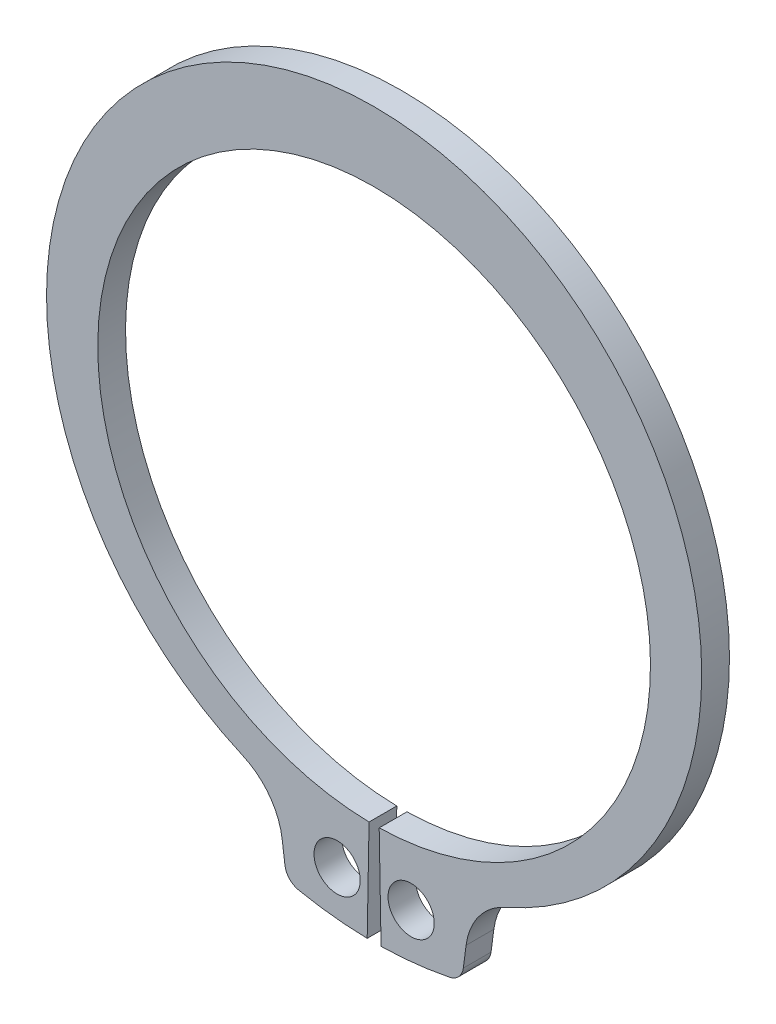
SolidWorks part; units mm, degrees
ref_plane "Plane1" through (0, 0, 0) normal (0, 0, 1) x (1, 0, 0)
ref_plane "Plane2" through (0, 0, 0) normal (0, 1, 0) x (1, 0, 0)
ref_plane "Plane3" through (0, 0, 0) normal (1, 0, 0) x (0, 0, -1)
sketch "Clipboard" plane through (0, 0, 0) normal (0, 0, 1) x (1, 0, 0)
  line L0 (0, 0) -> (3, 0)
  line L1 (0, 0) -> (0, 1.5)
  line L2 (0, 0) -> (0, -4.4)
  circle A0 centre (0, 0) radius 1
  circle A1 centre (0, 0) radius 12.5
sketch "BodySke" plane through (0, 0, 0) normal (0, 0, 1) x (1, 0, 0)
  line L0 (-1.5431, 0) -> (1.5431, 0) construction
  line L1 (0, 0) -> (0, 14.95) construction
  line L2 (0.2193, -11.948) -> (0.3, -16.3472)
  line L3 (-0.2193, -11.948) -> (-0.3, -16.3472)
  line L4 (0, 0) -> (6.8515, -14.8452) construction
  line L5 (0, 0) -> (-6.8515, -14.8452) construction
  line L7 (3.9769, -14.4667) -> (3.8561, -15.3842)
  line L8 (-3.9769, -14.4667) -> (-3.8561, -15.3842)
  circle A0 centre (0, 0) radius 11.95 construction
  arc A1 (0.2193, -11.948) -> (-0.2193, -11.948) centre (0, 0) ccw
  arc A2 (5.6362, -12.2121) -> (-5.6362, -12.2121) centre (0, 0.7842) ccw construction
  arc A3 (0.3, -16.3472) -> (3.2622, -16.0213) centre (0, 0) ccw
  arc A4 (5.6874, -12.1898) -> (3.9769, -14.4667) centre (6.8515, -14.8452) ccw
  arc A5 (-3.9769, -14.4667) -> (-5.6874, -12.1898) centre (-6.8515, -14.8452) ccw
  arc A6 (-3.2622, -16.0213) -> (-0.3, -16.3472) centre (0, 0) ccw
  arc A7 (5.6874, -12.1898) -> (-5.6874, -12.1898) centre (0, 0.7842) ccw
  arc A8 (-4.0592, -13.8421) -> (4.0592, -13.8421) centre (0, 0) ccw construction
  circle A9 centre (1.6, -14.336) radius 1
  circle A10 centre (-1.6, -14.336) radius 1
  arc A11 (3.8561, -15.3842) -> (3.2622, -16.0213) centre (3.1126, -15.2863) cw
  arc A12 (-3.8561, -15.3842) -> (-3.2622, -16.0213) centre (-3.1126, -15.2863) ccw
  point P28 (3.7876, -15.9052)
  point P31 (-3.7876, -15.9052)
  dimension "D3" = 0.75
  dimension "D2" = 15
extrude "Body" add sketch "BodySke" against normal blind 1.2
sketch "NotSke" plane through (0, 0, 0) normal (0, 0, 1) x (1, 0, 0)
  line L0 (1.6, -13.336) -> (1.6, -15.336)
  line L1 (1.6, -15.336) -> (-1.6, -15.336)
  line L2 (-1.6, -15.336) -> (-1.6, -13.336)
  line L3 (-1.6, -13.336) -> (1.6, -13.336)
  circle A0 centre (1.6, -14.336) radius 1 construction
  circle A1 centre (-1.6, -14.336) radius 1 construction
extrude "Notch" [suppressed] cut sketch "NotSke" against normal through all
sketch "UnlSke" plane through (0, 0, 0) normal (0, 0, 1) x (1, 0, 0)
  line L0 (-2.9356, -16.0843) -> (-2.1456, -11.7558)
  line L1 (2.9356, -16.0843) -> (2.1456, -11.7558)
  arc A0 (2.1456, -11.7558) -> (-2.1456, -11.7558) centre (0, 0) ccw
  arc A1 (2.9356, -16.0843) -> (-2.9356, -16.0843) centre (0, 0) ccw
  arc A2 (0.3, -16.3472) -> (3.2622, -16.0213) centre (0, 0) ccw construction
  arc A3 (0.2193, -11.948) -> (-0.2193, -11.948) centre (0, 0) ccw construction
  circle A4 centre (-1.6, -14.336) radius 1 construction
  circle A5 centre (1.6, -14.336) radius 1 construction
extrude "Unlug" [suppressed] add sketch "UnlSke" against normal through all
equation "' \"ShaftDia@Clipboard\" = 3"
equation "' \"Thickness@Body\" = 0.4"
equation "' \"GrooveDia@BodySke\" = 2.8"
equation "' \"LugSection@Clipboard\" = 1.9"
equation "' \"LargeSection@Clipboard\" = 0.8"
equation "' \"HoleDia@Clipboard\" = 1.0"
equation "' \"ShaftDia@Clipboard\" = 10"
equation "' \"Thickness@Body\" = 1.0"
equation "' \"GrooveDia@BodySke\" = 9.6"
equation "' \"LugSection@Clipboard\" = 3.3"
equation "' \"LargeSection@Clipboard\" = 1.8"
equation "' \"HoleDia@Clipboard\" = 1.5"
equation "\"SmallSection@Clipboard\" = \"LargeSection@Clipboard\" * 0.5"
equation "\"Gap@BodySke\" =  \"Thickness@Body\" / 2"
equation "\"LargeRad@BodySke\" =  \"GrooveDia@BodySke\" / 2 +  \"LargeSection@Clipboard\""
equation "\"SmallRad@BodySke\" =  \"GrooveDia@BodySke\" / 2 +  \"SmallSection@Clipboard\""
equation "\"LugRad@BodySke\" = \"GrooveDia@BodySke\" / 2 + \"LugSection@Clipboard\""
equation "\"HoleOffsetRad@BodySke\" = (  \"ShaftDia@Clipboard\" / 2 + \"LugRad@BodySke\" ) / 2"
equation "\"HoleSpacing@BodySke\" = \"Gap@BodySke\"  * 2 +  \"HoleDia@Clipboard\""
equation "\"HoleDia@BodySke\" =  \"HoleDia@Clipboard\""
equation "\"SmallAngle@BodySke\" = atn(\"HoleSpacing@BodySke\" / 2 / sqr(\"HoleOffsetRad@BodySke\"  * \"HoleOffsetRad@BodySke\" - (\"HoleSpacing@BodySke\" / 2) * (\"HoleSpacing@BodySke\" / 2) ))  * 7 *  (\"LargeRad@BodySke\" / \"SmallRad@BodySke\")* ( 180 / 3.141593)"
